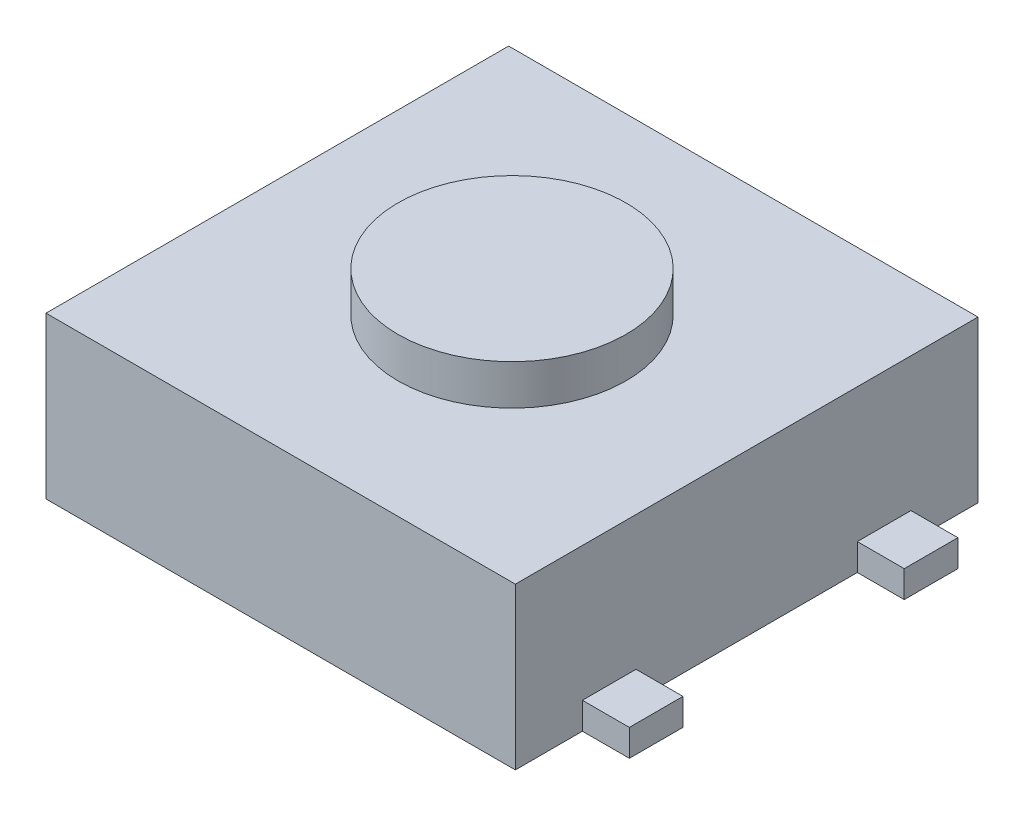
SolidWorks part; units mm, degrees
ref_plane "Спереди" through (0, 0, 0) normal (0, 0, 1) x (1, 0, 0)
ref_plane "Сверху" through (0, 0, 0) normal (0, 1, 0) x (1, 0, 0)
ref_plane "Справа" through (0, 0, 0) normal (1, 0, 0) x (0, 0, -1)
sketch "Эскиз2" plane through (0, 0, 0) normal (0, 1, 0) x (1, 0, 0)
  line L1 (-1.75, -1.725) -> (1.75, -1.725)
  line L2 (-1.75, -1.725) -> (-1.75, 1.725)
  line L3 (-1.75, 1.725) -> (1.75, 1.725)
  line L4 (1.75, -1.725) -> (1.75, 1.725)
  line L5 (-1.75, -1.725) -> (1.75, 1.725) construction
  line L6 (-1.75, 1.725) -> (1.75, -1.725) construction
  point P0 (0, 0)
  dimension "D1" = 3.45
  dimension "D2" = 3.5
extrude "Бобышка-Вытянуть1" add sketch "Эскиз2" along normal blind 1.5
sketch "Эскиз3" plane through (0, 0, 0) normal (0, -1, 0) x (-1, 0, 0)
  line L0 (1.75, 1.725) -> (1.75, -1.725) construction
  line L1 (1.75, -1.225) -> (2.1, -1.225)
  line L2 (1.75, -1.225) -> (1.75, -0.825)
  line L3 (1.75, -0.825) -> (2.1, -0.825)
  line L4 (2.1, -1.225) -> (2.1, -0.825)
  line L5 (2.1, -1.025) -> (1.75, -1.025) construction
  line L6 (1.75, 0.825) -> (2.1, 0.825)
  line L7 (1.75, 0.825) -> (1.75, 1.225)
  line L8 (1.75, 1.225) -> (2.1, 1.225)
  line L9 (2.1, 0.825) -> (2.1, 1.225)
  line L10 (2.1, 1.025) -> (1.75, 1.025) construction
  line L11 (1.75, -1.025) -> (1.75, 1.025) construction
  line L12 (-1.75, -1.725) -> (-1.75, 1.725) construction
  line L13 (-1.75, -1.225) -> (-2.1, -1.225)
  line L14 (-1.75, -1.225) -> (-1.75, -0.825)
  line L15 (-1.75, -0.825) -> (-2.1, -0.825)
  line L16 (-2.1, -1.225) -> (-2.1, -0.825)
  line L18 (-1.75, 0.825) -> (-2.1, 0.825)
  line L19 (-1.75, 0.825) -> (-1.75, 1.225)
  line L20 (-1.75, 1.225) -> (-2.1, 1.225)
  line L21 (-2.1, 0.825) -> (-2.1, 1.225)
  point P14 (1.75, 0)
  point P15 (1.75, 0)
  dimension "D1" = 0.4
  dimension "D2" = 2.05
  dimension "D3" = 4.2
extrude "Бобышка-Вытянуть2" add sketch "Эскиз3" against normal blind 0.2
sketch "Эскиз4" plane through (0, 1.5, 0) normal (0, 1, 0) x (1, 0, 0)
  line L1 (-1.75, -1.725) -> (1.75, -1.725)
  line L2 (-1.75, -1.725) -> (-1.75, 1.725)
  line L3 (-1.75, 1.725) -> (1.75, 1.725)
  line L4 (1.75, -1.725) -> (1.75, 1.725)
  circle A0 centre (0, 0) radius 0.85
  dimension "D1" = 1.7
extrude "Вырез-Вытянуть1" cut sketch "Эскиз4" against normal blind 0.3
